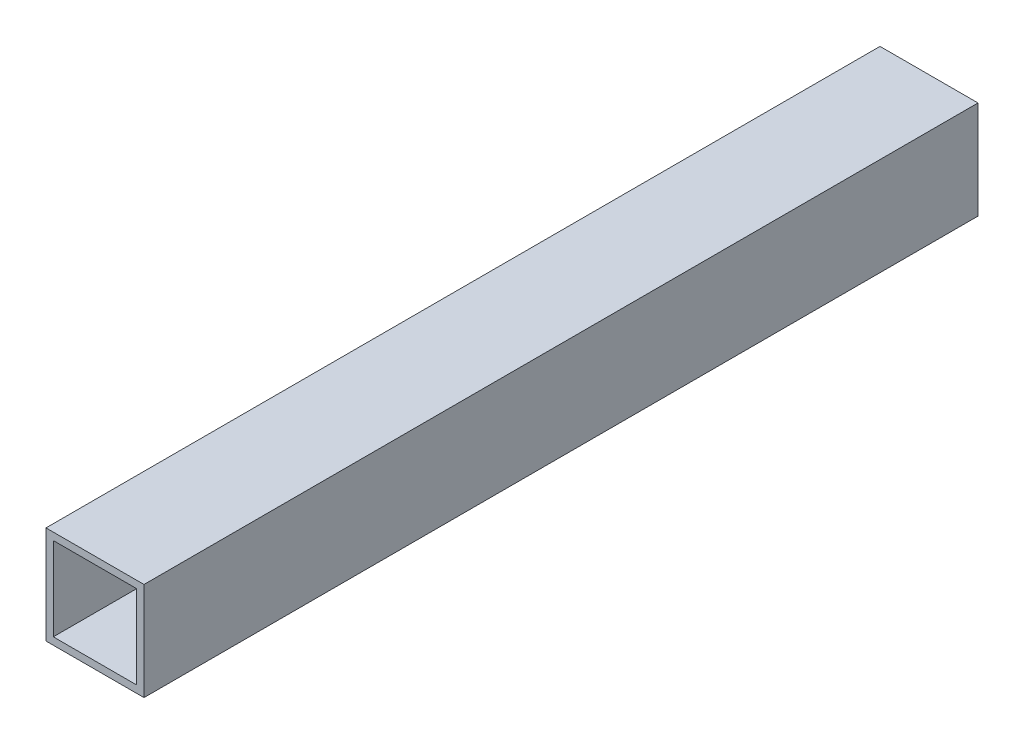
SolidWorks part; units mm, degrees
ref_plane "Plan de face" through (0, 0, 0) normal (0, 0, 1) x (1, 0, 0)
ref_plane "Plan de dessus" through (0, 0, 0) normal (0, 1, 0) x (1, 0, 0)
ref_plane "Plan de droite" through (0, 0, 0) normal (1, 0, 0) x (0, 0, -1)
sketch "Esquisse1" plane through (0, 0, 0) normal (0, 0, 1) x (1, 0, 0)
  line L1 (-11.75, -11.75) -> (11.75, -11.75)
  line L2 (-11.75, -11.75) -> (-11.75, 11.75)
  line L3 (-11.75, 11.75) -> (11.75, 11.75)
  line L4 (11.75, -11.75) -> (11.75, 11.75)
  line L5 (-11.75, -11.75) -> (11.75, 11.75) construction
  line L6 (-11.75, 11.75) -> (11.75, -11.75) construction
  line L7 (-10, -10) -> (10, -10)
  line L8 (-10, -10) -> (-10, 10)
  line L9 (-10, 10) -> (10, 10)
  line L10 (10, -10) -> (10, 10)
  line L11 (-10, -10) -> (10, 10) construction
  line L12 (-10, 10) -> (10, -10) construction
  point P1 (0, 0)
  point P6 (0, 0)
  dimension "D1" = 20
  dimension "D2" = 23.5
extrude "Boss.-Extru.1" add sketch "Esquisse1" along normal blind 200
sketch "Esquisse2" plane through (-11.75, 0, 0) normal (-1, 0, 0) x (0, 0, 1)
  line L0 (0, -11.75) -> (200, 11.75) construction
  line L1 (0, 11.75) -> (200, -11.75) construction
  line L2 (200, -11.75) -> (0, -11.75) construction
  circle A0 centre (100, 0) radius 7.2103
extrude "Enlèv. mat.-Extru.1" cut sketch "Esquisse2" against normal up to vertex (1.75 mm away)
